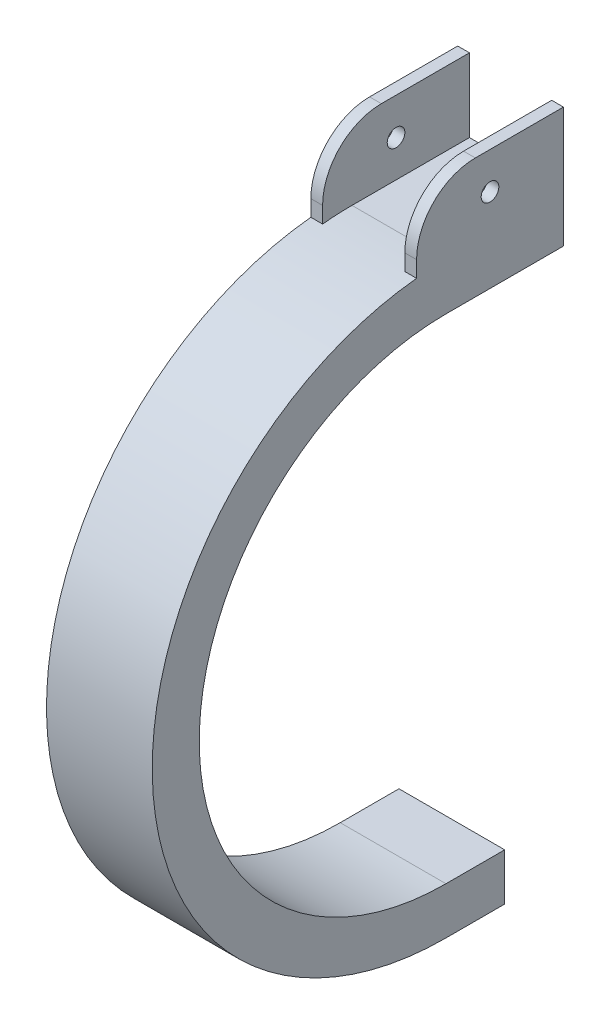
SolidWorks part; units mm, degrees
ref_plane "Front Plane" through (0, 0, 0) normal (0, 0, 1) x (1, 0, 0)
ref_plane "Top Plane" through (0, 0, 0) normal (0, 1, 0) x (1, 0, 0)
ref_plane "Right Plane" through (0, 0, 0) normal (1, 0, 0) x (0, 0, -1)
sketch "Sketch1" plane through (0, 0, 0) normal (1, 0, 0) x (0, 0, -1)
  line L3 (0, -42) -> (10, -42)
  line L5 (0, -50) -> (10, -50)
  line L6 (10, -42) -> (10, -50)
  line L7 (0, 50) -> (20, 50)
  line L9 (0, 42) -> (20, 42)
  line L10 (20, 50) -> (20, 42)
  arc A0 (0, 50) -> (0, -50) centre (0, 0) ccw
  arc A1 (0, 42) -> (0, -42) centre (0, 0) ccw
  dimension "D1" = 100
  dimension "D2" = 8
  dimension "D3" = 20
  dimension "D4" = 10
extrude "Boss-Extrude1" add sketch "Sketch1" along normal blind 18
sketch "Sketch2" plane through (18, 0, 0) normal (1, 0, 0) x (0, 0, -1)
  line L0 (20, 42) -> (20, 50) construction
  line L1 (20, 46) -> (-5, 46)
  line L2 (20, 46) -> (20, 62.5)
  line L3 (20, 62.5) -> (-5, 62.5)
  line L4 (-5, 46) -> (-5, 62.5)
  line L5 (20, 50) -> (0, 50) construction
  dimension "D1" = 25
  dimension "D2" = 12.5
extrude "Boss-Extrude2" add sketch "Sketch2" against normal blind 2
sketch "Sketch3" plane through (0, 0, 0) normal (-1, 0, 0) x (0, 0, 1)
  line L0 (-20, 42) -> (-20, 50) construction
  line L1 (-20, 46) -> (5, 46)
  line L2 (-20, 46) -> (-20, 62.5)
  line L3 (-20, 62.5) -> (5, 62.5)
  line L4 (5, 46) -> (5, 62.5)
  line L5 (-20, 50) -> (0, 50) construction
  dimension "D1" = 25
  dimension "D2" = 12.5
extrude "Boss-Extrude3" add sketch "Sketch3" against normal blind 2
sketch "Sketch4" plane through (0, 0, 0) normal (-1, 0, 0) x (0, 0, 1)
  line L0 (5, 62.5) -> (-20, 62.5) construction
  circle A0 centre (-7.5, 56.25) radius 1.5
  dimension "D1" = 3
  dimension "D2" = 6.25
extrude "Cut-Extrude1" cut sketch "Sketch4" against normal blind 32
fillet "Fillet1" radius 10 2 edges at (17, 62.5, 5) (1, 62.5, 5)
